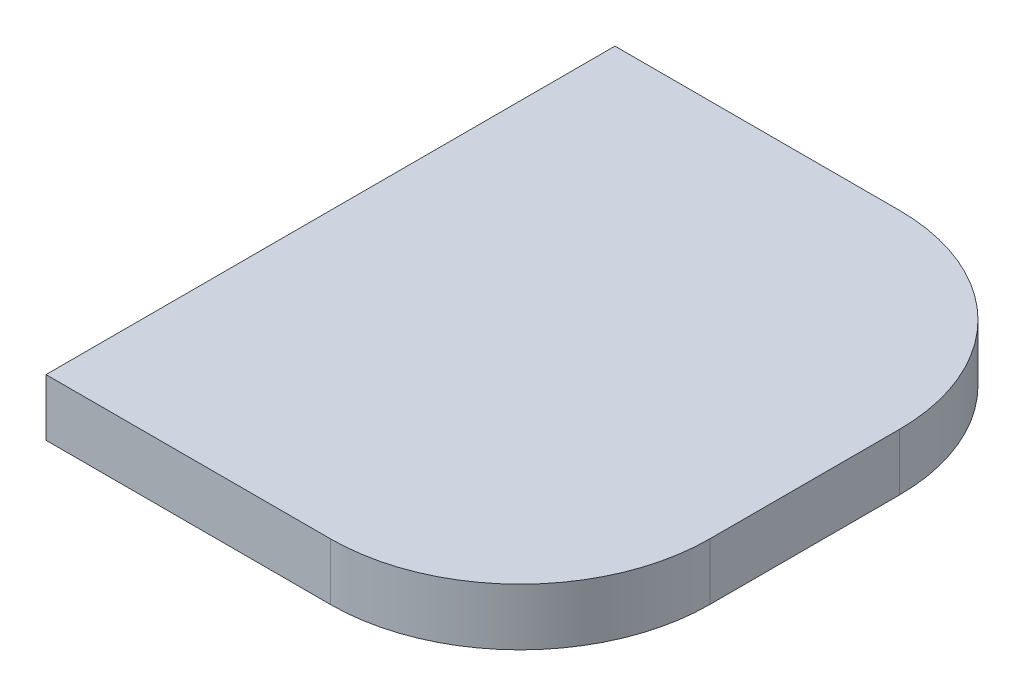
SolidWorks part; units mm, degrees
material "PE Low/Medium Density"
ref_plane "Front Plane" through (0, 0, 0) normal (0, 0, 1) x (1, 0, 0)
ref_plane "Top Plane" through (0, 0, 0) normal (0, 1, 0) x (1, 0, 0)
ref_plane "Right Plane" through (0, 0, 0) normal (1, 0, 0) x (0, 0, -1)
sketch "Sketch1" plane through (0, 0, 0) normal (0, 1, 0) x (1, 0, 0)
  line L1 (2.5, -15) -> (-12.5, -15)
  line L2 (12.5, -5) -> (12.5, 5)
  line L3 (2.5, 15) -> (-12.5, 15)
  line L4 (-12.5, -15) -> (-12.5, 15)
  line L5 (12.5, -15) -> (-12.5, 15) construction
  line L6 (12.5, 15) -> (-12.5, -15) construction
  arc A0 (2.5, -15) -> (12.5, -5) centre (2.5, -5) ccw
  arc A1 (12.5, 5) -> (2.5, 15) centre (2.5, 5) ccw
  point P0 (0, 0)
  dimension "D3" = 10
  dimension "D1" = 25
  dimension "D2" = 30
extrude "Boss-Extrude1" add sketch "Sketch1" along normal blind 3
